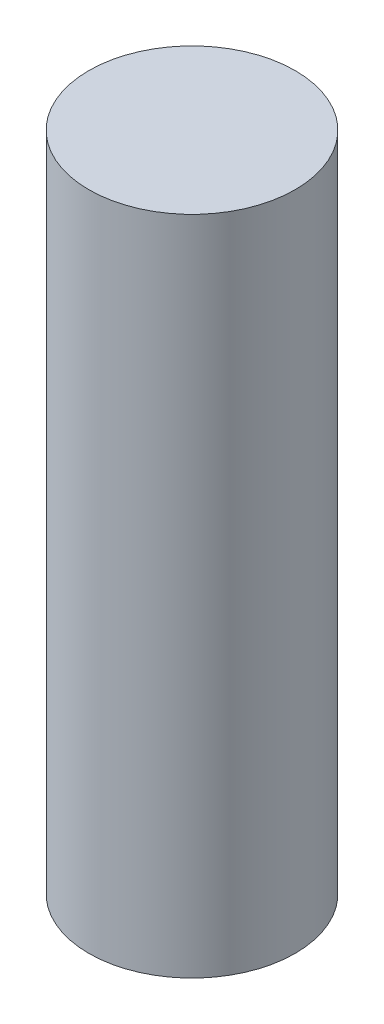
SolidWorks part; units mm, degrees
ref_plane "Alzado" through (0, 0, 0) normal (0, 0, 1) x (1, 0, 0)
ref_plane "Planta" through (0, 0, 0) normal (0, 1, 0) x (1, 0, 0)
ref_plane "Vista lateral" through (0, 0, 0) normal (1, 0, 0) x (0, 0, -1)
sketch "Croquis1" plane through (0, 0, 0) normal (0, 1, 0) x (1, 0, 0)
  circle A0 centre (0, 0) radius 3.9624
  dimension "D1" = 7.9248
extrude "Saliente-Extruir1" add sketch "Croquis1" along normal blind 25.4
